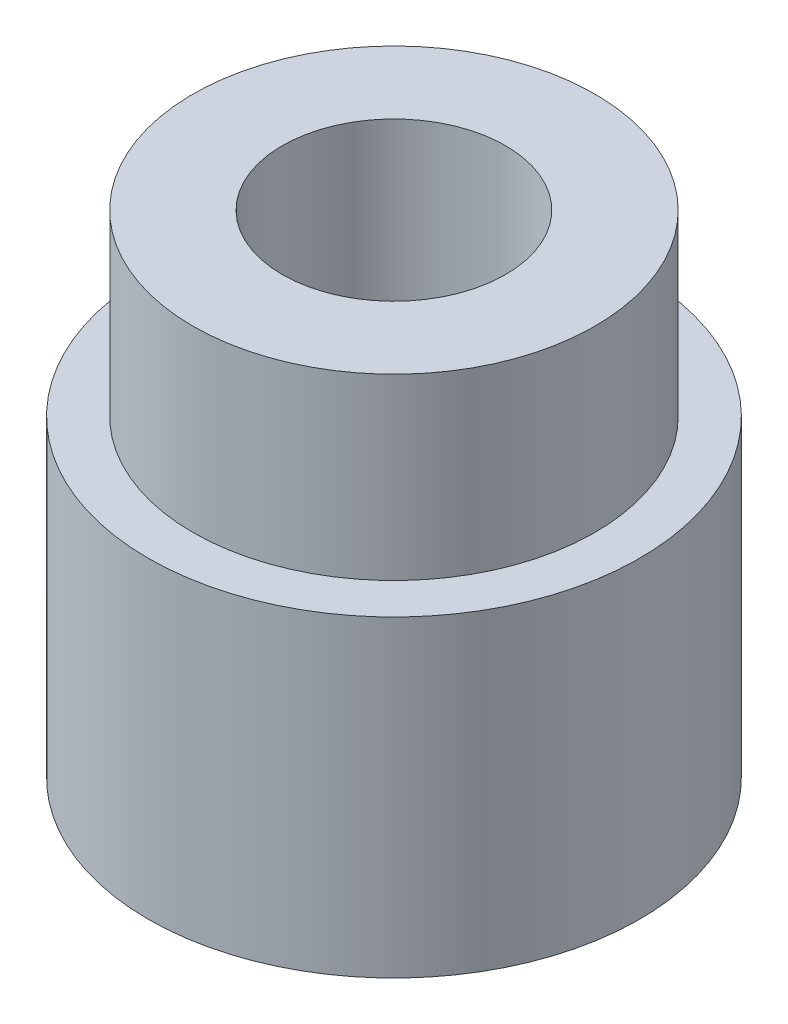
SolidWorks part; units mm, degrees
ref_plane "Plan de face" through (0, 0, 0) normal (0, 0, 1) x (1, 0, 0)
ref_plane "Plan de dessus" through (0, 0, 0) normal (0, 1, 0) x (1, 0, 0)
ref_plane "Plan de droite" through (0, 0, 0) normal (1, 0, 0) x (0, 0, -1)
sketch "Esquisse1" plane through (0, 0, 0) normal (0, 1, 0) x (1, 0, 0)
  circle A0 centre (0, 0) radius 5.5
extrude "Boss.-Extru.1" add sketch "Esquisse1" along normal blind 7
sketch "Esquisse9" plane through (0, 7, 0) normal (0, 1, 0) x (1, 0, 0)
  circle A0 centre (0, 0) radius 4.5
extrude "Boss.-Extru.3" add sketch "Esquisse9" along normal blind 4
sketch "Esquisse10" plane through (0, 11, 0) normal (0, 1, 0) x (1, 0, 0)
  circle A0 centre (0, 0) radius 2.5
extrude "Enlèv. mat.-Extru.4" cut sketch "Esquisse10" against normal blind 11
